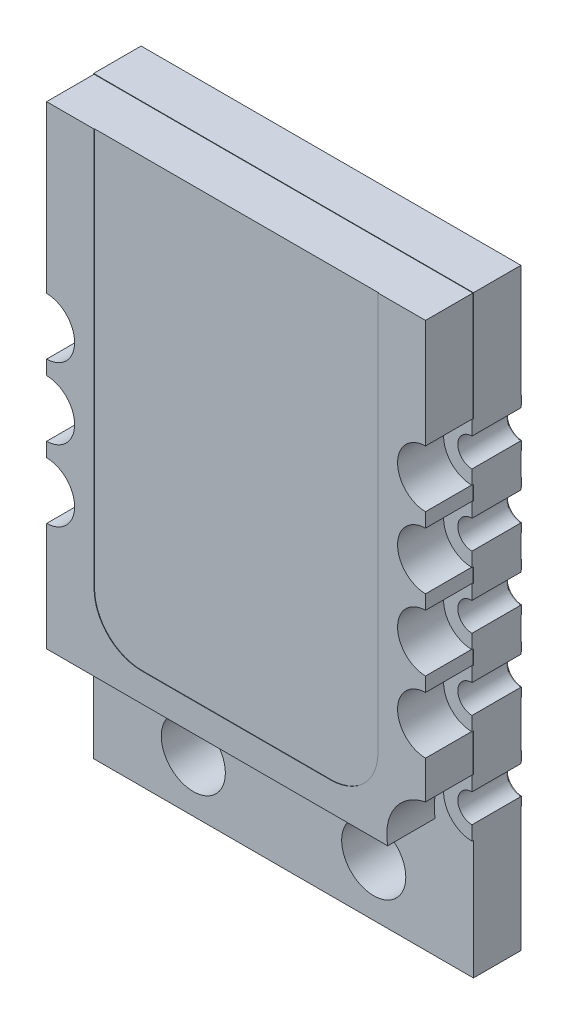
SolidWorks part; units mm, degrees
ref_plane "Front Plane" through (0, 0, 0) normal (0, 0, 1) x (1, 0, 0)
ref_plane "Top Plane" through (0, 0, 0) normal (0, 1, 0) x (1, 0, 0)
ref_plane "Right Plane" through (0, 0, 0) normal (1, 0, 0) x (0, 0, -1)
sketch "Sketch1" plane through (0, 0, 0) normal (0, 0, 1) x (1, 0, 0)
  line L0 (27.8, 30.075) -> (35.7999, 30.075)
  line L1 (35.7999, 30.075) -> (35.7999, 42.575)
  line L2 (27.8, 30.075) -> (27.8, 42.575)
  line L3 (27.8, 42.575) -> (35.7999, 42.575)
  circle A0 centre (33.9979, 35.6362) radius 0.1
  circle A1 centre (31.242, 33.7312) radius 0.1
  circle A2 centre (28.6512, 34.2519) radius 0.1
  circle A3 centre (28.6766, 39.4589) radius 0.1
  circle A4 centre (35.1282, 41.0718) radius 0.1
  circle A5 centre (28.5623, 41.0718) radius 0.1
  circle A6 centre (29.4894, 37.4523) radius 0.1
  circle A7 centre (34.417, 40.3987) radius 0.1
  circle A8 centre (28.6766, 40.1955) radius 0.1
  circle A9 centre (29.9, 31.2) radius 0.675
  circle A10 centre (33.7, 31.2) radius 0.675
  circle A11 centre (27.8003, 35.4711) radius 0.3
  circle A12 centre (27.8003, 38.4683) radius 0.3
  circle A13 centre (35.8013, 33.1851) radius 0.3
  circle A14 centre (35.8013, 35.179) radius 0.3
  circle A15 centre (35.8013, 38.1762) radius 0.3
  circle A16 centre (35.8013, 39.6748) radius 0.3
  circle A17 centre (35.8013, 36.6776) radius 0.3
  circle A18 centre (27.8003, 36.9697) radius 0.3
extrude "Boss-Extrude1" add sketch "Sketch1" along normal blind 1 contours A18 L2 A11 L0 L1 A13 A14 A17 A15 A16 L3 A12 A10 A9 A8 A7 A6 A5 A4 A3 A2 A1 A0
sketch "Sketch6" plane through (0, 0, 0) normal (0, 0, -1) x (-1, 0, 0)
  line L1 (-35.4319, 41.7135) -> (-28.3163, 41.7135)
  line L2 (-35.4319, 41.7135) -> (-35.4319, 32.8191)
  line L3 (-35.4319, 32.8191) -> (-28.3163, 32.8191)
  line L4 (-28.3163, 41.7135) -> (-28.3163, 32.8191)
extrude "Boss-Extrude5" add sketch "Sketch6" against normal blind 1
sketch "Sketch2" plane through (0, 0, 1) normal (0, 0, 1) x (1, 0, 0)
  line L0 (27.81, 32.5831) -> (34.9936, 32.5831)
  line L24 (27.81, 36.6599) -> (27.81, 35.7809)
  line L25 (27.81, 35.1613) -> (27.81, 30.085)
  line L26 (27.81, 30.085) -> (35.7899, 30.085)
  line L27 (35.7899, 30.085) -> (35.7899, 32.8753)
  line L28 (35.7899, 33.4949) -> (35.7899, 34.8692)
  line L29 (35.7899, 35.4888) -> (35.7899, 36.3678)
  line L30 (35.7899, 36.9874) -> (35.7899, 37.8664)
  line L31 (35.7899, 38.486) -> (35.7899, 39.365)
  line L32 (35.7899, 39.9846) -> (35.7899, 42.565)
  line L33 (35.7899, 42.565) -> (27.81, 42.565)
  line L34 (27.81, 42.565) -> (27.81, 38.7781)
  line L35 (27.81, 38.1585) -> (27.81, 37.2795)
  line L36 (27.81, 36.3703) -> (27.81, 36.0705)
  line L37 (27.81, 34.8717) -> (27.81, 32.5831)
  line L40 (35.7899, 33.7818) -> (35.7899, 34.5797)
  line L41 (35.7899, 35.7783) -> (35.7899, 36.0783)
  line L42 (35.7899, 37.2769) -> (35.7899, 37.5769)
  line L43 (35.7899, 38.7755) -> (35.7899, 39.0755)
  line L44 (35.7899, 40.2741) -> (35.7899, 42.565)
  line L45 (35.7899, 42.565) -> (27.81, 42.565)
  line L46 (27.81, 42.565) -> (27.81, 39.0677)
  line L47 (27.81, 37.8689) -> (27.81, 37.5691)
  arc A0 (35.7899, 33.7818) -> (34.9936, 32.5831) centre (35.9918, 32.7838) ccw
  arc A8 (27.81, 37.8689) -> (27.81, 39.0677) centre (27.8003, 38.4683) ccw
  arc A9 (27.81, 36.3703) -> (27.81, 37.5691) centre (27.8003, 36.9697) ccw
  arc A10 (27.81, 34.8717) -> (27.81, 36.0705) centre (27.8003, 35.4711) ccw
  arc A11 (35.7899, 40.2741) -> (35.7899, 39.0755) centre (35.8013, 39.6748) ccw
  arc A12 (35.7899, 38.7755) -> (35.7899, 37.5769) centre (35.8013, 38.1762) ccw
  arc A13 (35.7899, 37.2769) -> (35.7899, 36.0783) centre (35.8013, 36.6776) ccw
  arc A14 (35.7899, 35.7783) -> (35.7899, 34.5797) centre (35.8013, 35.179) ccw
  arc A16 (27.81, 36.6599) -> (27.81, 37.2795) centre (27.8003, 36.9697) ccw
  arc A17 (27.81, 35.1613) -> (27.81, 35.7809) centre (27.8003, 35.4711) ccw
  arc A18 (35.7899, 33.4949) -> (35.7899, 32.8753) centre (35.8013, 33.1851) ccw
  arc A19 (35.7899, 35.4888) -> (35.7899, 34.8692) centre (35.8013, 35.179) ccw
  arc A20 (35.7899, 36.9874) -> (35.7899, 36.3678) centre (35.8013, 36.6776) ccw
  arc A21 (35.7899, 38.486) -> (35.7899, 37.8664) centre (35.8013, 38.1762) ccw
  arc A22 (35.7899, 39.9846) -> (35.7899, 39.365) centre (35.8013, 39.6748) ccw
  arc A23 (27.81, 38.1585) -> (27.81, 38.7781) centre (27.8003, 38.4683) ccw
  dimension "D1" = 0.01
extrude "Boss-Extrude2" add sketch "Sketch2" along normal blind 1
sketch "Sketch3" plane through (0, 0, 2) normal (0, 0, 1) x (1, 0, 0)
  line L0 (27.81, 32.5831) -> (34.9936, 32.5831) construction
  line L1 (28.81, 42.7777) -> (34.7899, 42.7777)
  line L2 (28.81, 42.7777) -> (28.81, 34.1831)
  line L3 (29.81, 33.1831) -> (33.7899, 33.1831)
  line L4 (34.7899, 42.7777) -> (34.7899, 34.1831)
  line L5 (27.81, 34.8717) -> (27.81, 32.5831) construction
  line L6 (35.7899, 33.7818) -> (35.7899, 34.5797) construction
  arc A0 (33.7899, 33.1831) -> (34.7899, 34.1831) centre (33.7899, 34.1831) ccw
  arc A1 (28.81, 34.1831) -> (29.81, 33.1831) centre (29.81, 34.1831) ccw
  dimension "D4" = 1
  dimension "D1" = 0.6
  dimension "D2" = 1
  dimension "D3" = 1
extrude "Cut-Extrude1" cut sketch "Sketch3" against normal blind 0.01
sketch "Sketch4" plane through (0, 0, 0) normal (0, 0, -1) x (-1, 0, 0)
  line L12 (-35.7799, 33.6949) -> (-35.7799, 33.5044)
  line L13 (-35.7799, 35.6888) -> (-35.7799, 35.4983)
  line L14 (-35.7799, 37.1874) -> (-35.7799, 36.9969)
  line L15 (-35.7799, 38.686) -> (-35.7799, 38.4955)
  line L16 (-27.82, 37.9601) -> (-27.82, 38.1489)
  line L17 (-27.82, 36.4615) -> (-27.82, 36.6503)
  line L24 (-27.82, 37.2891) -> (-27.82, 38.1489)
  line L25 (-27.82, 38.7877) -> (-27.82, 42.555)
  line L26 (-27.82, 42.555) -> (-35.7799, 42.555)
  line L27 (-35.7799, 42.555) -> (-35.7799, 39.9941)
  line L28 (-35.7799, 39.3555) -> (-35.7799, 38.4955)
  line L29 (-35.7799, 37.8569) -> (-35.7799, 36.9969)
  line L30 (-35.7799, 36.3583) -> (-35.7799, 35.4983)
  line L31 (-35.7799, 34.8597) -> (-35.7799, 33.5044)
  line L32 (-35.7799, 32.8658) -> (-35.7799, 30.095)
  line L33 (-35.7799, 30.095) -> (-27.82, 30.095)
  line L34 (-27.82, 30.095) -> (-27.82, 35.1517)
  line L35 (-27.82, 35.7905) -> (-27.82, 36.6503)
  line L36 (-27.82, 37.2891) -> (-27.82, 37.4795)
  line L37 (-27.82, 38.7877) -> (-27.82, 38.9781)
  line L39 (-35.7799, 40.1846) -> (-35.7799, 39.9941)
  line L40 (-35.7799, 39.3555) -> (-35.7799, 39.1666)
  line L41 (-35.7799, 37.8569) -> (-35.7799, 37.668)
  line L42 (-35.7799, 36.3583) -> (-35.7799, 36.1694)
  line L43 (-35.7799, 34.8597) -> (-35.7799, 34.6708)
  line L44 (-35.7799, 32.8658) -> (-35.7799, 32.6769)
  line L46 (-27.82, 34.9629) -> (-27.82, 35.1517)
  line L47 (-27.82, 35.7905) -> (-27.82, 35.9809)
  line L49 (-35.7799, 39.1666) -> (-35.0388, 39.1666)
  line L50 (-35.0388, 40.1846) -> (-35.7799, 40.1846)
  line L55 (-35.7799, 37.668) -> (-35.0388, 37.668)
  line L56 (-35.0388, 38.686) -> (-35.7799, 38.686)
  line L57 (-35.7799, 36.1694) -> (-35.0388, 36.1694)
  line L58 (-35.0388, 37.1874) -> (-35.7799, 37.1874)
  line L59 (-35.7799, 34.6708) -> (-35.0388, 34.6708)
  line L60 (-35.0388, 35.6888) -> (-35.7799, 35.6888)
  line L61 (-35.7799, 32.6769) -> (-35.0388, 32.6769)
  line L62 (-35.0388, 33.6949) -> (-35.7799, 33.6949)
  line L63 (-27.82, 37.4795) -> (-28.5598, 37.4795)
  line L64 (-28.5588, 36.4615) -> (-27.82, 36.4615)
  line L65 (-28.5598, 34.9629) -> (-27.82, 34.9629)
  line L66 (-27.82, 35.9809) -> (-28.5588, 35.9809)
  line L67 (-28.5598, 37.9601) -> (-27.82, 37.9601)
  line L68 (-27.82, 38.9781) -> (-28.5588, 38.9781)
  arc A17 (-27.82, 37.2891) -> (-27.82, 36.6503) centre (-27.8003, 36.9697) ccw
  arc A18 (-27.82, 38.7877) -> (-27.82, 38.1489) centre (-27.8003, 38.4683) ccw
  arc A19 (-35.7799, 39.3555) -> (-35.7799, 39.9941) centre (-35.8013, 39.6748) ccw
  arc A20 (-35.7799, 37.8569) -> (-35.7799, 38.4955) centre (-35.8013, 38.1762) ccw
  arc A21 (-35.7799, 36.3583) -> (-35.7799, 36.9969) centre (-35.8013, 36.6776) ccw
  arc A22 (-35.7799, 34.8597) -> (-35.7799, 35.4983) centre (-35.8013, 35.179) ccw
  arc A23 (-35.7799, 32.8658) -> (-35.7799, 33.5044) centre (-35.8013, 33.1851) ccw
  arc A24 (-27.82, 35.7905) -> (-27.82, 35.1517) centre (-27.8003, 35.4711) ccw
  arc A25 (-27.82, 37.2891) -> (-27.82, 36.6503) centre (-27.8003, 36.9697) ccw
  arc A26 (-27.82, 38.7877) -> (-27.82, 38.1489) centre (-27.8003, 38.4683) ccw
  arc A27 (-35.7799, 39.3555) -> (-35.7799, 39.9941) centre (-35.8013, 39.6748) ccw
  arc A28 (-35.7799, 37.8569) -> (-35.7799, 38.4955) centre (-35.8013, 38.1762) ccw
  arc A29 (-35.7799, 36.3583) -> (-35.7799, 36.9969) centre (-35.8013, 36.6776) ccw
  arc A30 (-35.7799, 34.8597) -> (-35.7799, 35.4983) centre (-35.8013, 35.179) ccw
  arc A31 (-35.7799, 32.8658) -> (-35.7799, 33.5044) centre (-35.8013, 33.1851) ccw
  arc A32 (-27.82, 35.7905) -> (-27.82, 35.1517) centre (-27.8003, 35.4711) ccw
  arc A50 (-35.0388, 39.1666) -> (-35.0388, 40.1846) centre (-35.0388, 39.6756) ccw
  arc A52 (-35.0388, 37.668) -> (-35.0388, 38.686) centre (-35.0388, 38.177) ccw
  arc A54 (-35.0388, 36.1694) -> (-35.0388, 37.1874) centre (-35.0388, 36.6784) ccw
  arc A56 (-35.0388, 34.6708) -> (-35.0388, 35.6888) centre (-35.0388, 35.1798) ccw
  arc A58 (-35.0388, 32.6769) -> (-35.0388, 33.6949) centre (-35.0388, 33.1859) ccw
  arc A60 (-28.5598, 37.4795) -> (-28.5588, 36.4615) centre (-28.5588, 36.9705) ccw
  arc A63 (-28.5588, 35.9809) -> (-28.5598, 34.9629) centre (-28.5588, 35.4719) ccw
  arc A65 (-28.5588, 38.9781) -> (-28.5598, 37.9601) centre (-28.5588, 38.4691) ccw
  dimension "D1" = 0.02
extrude "Boss-Extrude3" add sketch "Sketch4" along normal blind 0.03
sketch "Sketch5" plane through (0, 0, 1) normal (0, 0, 1) x (1, 0, 0)
  line L1 (35.7999, 39.3748) -> (35.7999, 39.0754)
  line L2 (27.8, 39.0677) -> (27.8, 38.7683)
  line L3 (35.7999, 37.8762) -> (35.7999, 37.5768)
  line L4 (35.7999, 40.2742) -> (35.7999, 39.9748)
  line L5 (35.7999, 38.7756) -> (35.7999, 38.4762)
  line L6 (35.7999, 36.3776) -> (35.7999, 36.0782)
  line L7 (35.7999, 37.277) -> (35.7999, 36.9776)
  line L8 (35.7999, 34.879) -> (35.7999, 34.5796)
  line L9 (35.7999, 35.7784) -> (35.7999, 35.479)
  line L10 (35.7999, 32.8851) -> (35.7999, 32.5857)
  line L11 (35.7999, 33.7845) -> (35.7999, 33.4851)
  line L12 (27.8, 35.1683) -> (27.8, 34.8689)
  line L13 (27.8, 36.0677) -> (27.8, 35.7683)
  line L14 (27.8, 36.6683) -> (27.8, 36.3689)
  line L15 (27.8, 37.5677) -> (27.8, 37.2683)
  line L16 (27.8, 38.1683) -> (27.8, 37.8689)
  arc A0 (35.7999, 33.4851) -> (35.7999, 32.8851) centre (35.8013, 33.1851) ccw
  arc A1 (35.7999, 33.7845) -> (35.7999, 32.5857) centre (35.8013, 33.1851) ccw
  arc A2 (35.7999, 39.9748) -> (35.7999, 39.3748) centre (35.8013, 39.6748) ccw
  arc A3 (35.7999, 40.2742) -> (35.7999, 39.0754) centre (35.8013, 39.6748) ccw
  arc A8 (27.8, 38.1683) -> (27.8, 38.7683) centre (27.8003, 38.4683) ccw
  arc A9 (27.8, 37.8689) -> (27.8, 39.0677) centre (27.8003, 38.4683) ccw
  arc A10 (35.7999, 38.4762) -> (35.7999, 37.8762) centre (35.8013, 38.1762) ccw
  arc A11 (35.7999, 38.7756) -> (35.7999, 37.5768) centre (35.8013, 38.1762) ccw
  arc A12 (35.7999, 36.9776) -> (35.7999, 36.3776) centre (35.8013, 36.6776) ccw
  arc A13 (35.7999, 37.277) -> (35.7999, 36.0782) centre (35.8013, 36.6776) ccw
  arc A14 (35.7999, 35.479) -> (35.7999, 34.879) centre (35.8013, 35.179) ccw
  arc A15 (35.7999, 35.7784) -> (35.7999, 34.5796) centre (35.8013, 35.179) ccw
  arc A16 (27.8, 36.6683) -> (27.8, 37.2683) centre (27.8, 36.9683) ccw
  arc A17 (27.8, 36.3689) -> (27.8, 37.5677) centre (27.8, 36.9683) ccw
  arc A18 (27.8, 35.1683) -> (27.8, 35.7683) centre (27.8, 35.4683) ccw
  arc A19 (27.8, 34.8689) -> (27.8, 36.0677) centre (27.8, 35.4683) ccw
extrude "Boss-Extrude4" add sketch "Sketch5" along normal blind 0.03
